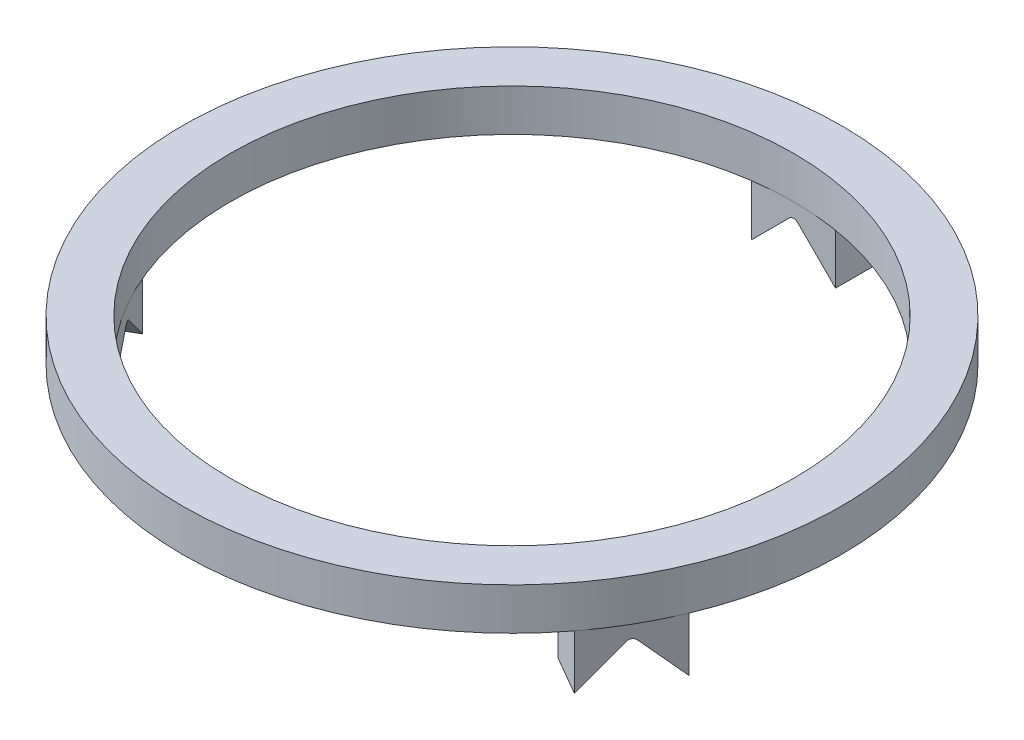
SolidWorks part; units mm, degrees
ref_plane "Front Plane" through (0, 0, 0) normal (0, 0, 1) x (1, 0, 0)
ref_plane "Top Plane" through (0, 0, 0) normal (0, 1, 0) x (1, 0, 0)
ref_plane "Right Plane" through (0, 0, 0) normal (1, 0, 0) x (0, 0, -1)
sketch "Sketch1" plane through (0, 0, 0) normal (0, 1, 0) x (1, 0, 0)
  circle A0 centre (0, 0) radius 11.938
  circle A1 centre (0, 0) radius 13.97
extrude "Boss-Extrude1" add sketch "Sketch1" along normal blind 1.778
ref_plane "Plane1" through (0, 0, 0) normal (0, -1, 0) x (-1, 0, 0)
sketch "Sketch3" plane through (0, 0, 0) normal (0, -1, 0) x (-1, 0, 0)
  line L0 (0, 11.938) -> (-1.778, 11.938)
  line L1 (-1.778, 11.938) -> (-1.778, 13.8564)
  line L2 (-1.778, 13.8564) -> (1.778, 13.8564)
  line L3 (1.778, 13.8564) -> (1.778, 11.938)
  line L4 (1.778, 11.938) -> (0, 11.938)
  circle A0 centre (0, 0) radius 11.938 construction
  circle A4 centre (0, 0) radius 13.97 construction
extrude "Boss-Extrude2" add sketch "Sketch3" along normal blind 2.286
sketch "Sketch4" plane through (0, 0, -11.938) normal (0, 0, 1) x (1, 0, 0)
  line L0 (-1.778, -2.286) -> (0, -0.508)
  line L1 (0, -0.508) -> (1.778, -2.286)
  line L2 (1.778, -2.286) -> (-1.778, -2.286)
extrude "Cut-Extrude1" cut sketch "Sketch4" against normal blind 2.54
fillet "Fillet2" radius 0.254 1 edges at (0, -0.508, -12.8972)
pattern_circular "CirPattern2" count 3 every 120 about axis through (0, 0, 0) along (0, 1, 0) of "Boss-Extrude2", "Cut-Extrude1", "Fillet2"
